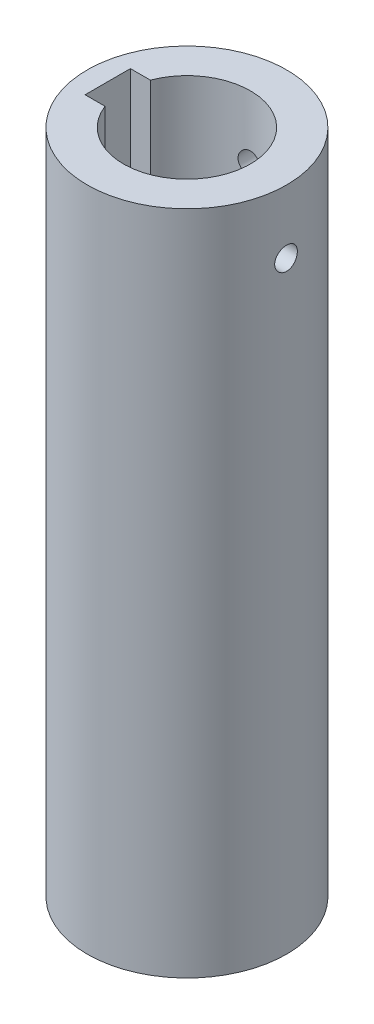
SolidWorks part; units mm, degrees
material "AISI 304"
ref_plane "Front Plane" through (0, 0, 0) normal (0, 0, 1) x (1, 0, 0)
ref_plane "Top Plane" through (0, 0, 0) normal (0, 1, 0) x (1, 0, 0)
ref_plane "Right Plane" through (0, 0, 0) normal (1, 0, 0) x (0, 0, -1)
sketch "Sketch1" plane through (0, 0, 0) normal (0, 1, 0) x (1, 0, 0)
  circle A0 centre (0, 0) radius 11
  circle A1 centre (0, 0) radius 7
  dimension "D1" = 22
  dimension "D2" = 14
extrude "Boss-Extrude1" add sketch "Sketch1" along normal mid plane 73.5
ref_plane "Plane1" through (0, 0, -11) normal (0, 0, -1) x (-1, 0, 0)
sketch "Sketch2" plane through (0, 0, -11) normal (0, 0, -1) x (-1, 0, 0)
  line L0 (11, 36.75) -> (-11, 36.75) construction
  circle A0 centre (0, 29.75) radius 1.25
  dimension "D1" = 2.5
  dimension "D2" = 7
extrude "Cut-Extrude1" cut sketch "Sketch2" against normal blind 10
pattern_circular "CirPattern1" count 2 over 90 about axis through (0, 36.75, 0) along (0, -1, 0) of "Cut-Extrude1"
ref_plane "Plane2" through (0, 0, 7) normal (0, 0, -1) x (-1, 0, 0)
sketch "Sketch4" plane through (0, 36.75, 0) normal (0, 1, 0) x (1, 0, 0)
  line L0 (-6.5383, 2.5) -> (-8.7383, 2.5)
  line L1 (-6.5383, -2.5) -> (-8.7383, -2.5)
  line L2 (-8.7383, 2.5) -> (-8.7383, -2.5)
  line L3 (-8.7383, 0) -> (0, 0) construction
  arc A0 (-6.5383, -2.5) -> (-6.5653, 2.4283) centre (0, 0) cw
  circle A1 centre (0, 0) radius 7 construction
  dimension "D1" = 5
  dimension "D2" = 2.2
extrude "Cut-Extrude2" cut sketch "Sketch4" against normal through all both and the other way through all
